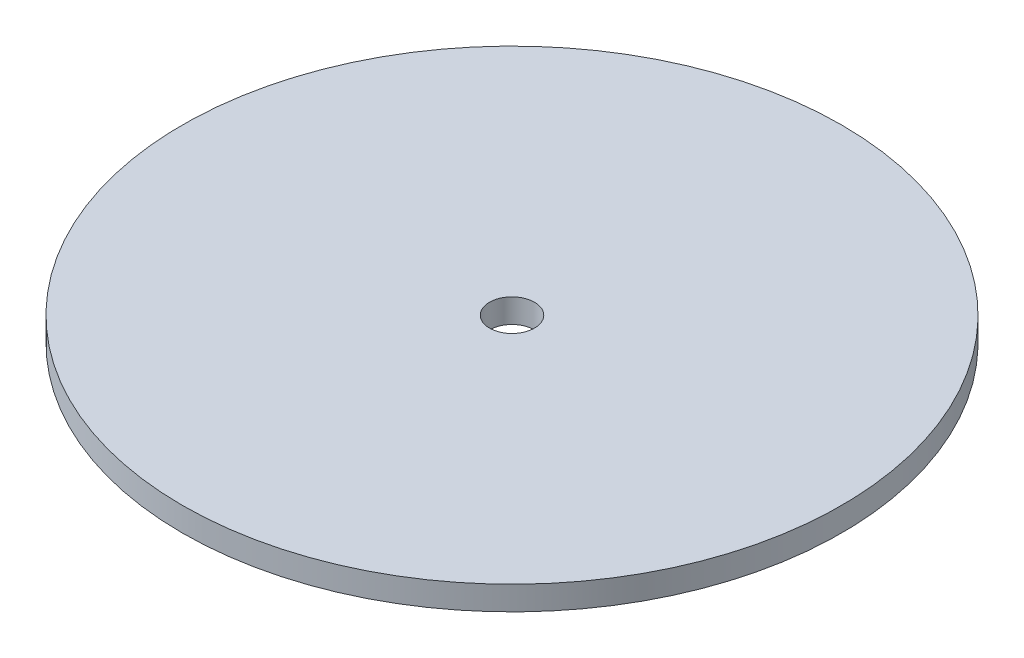
SolidWorks part; units mm, degrees
ref_plane "Front Plane" through (0, 0, 0) normal (0, 0, 1) x (1, 0, 0)
ref_plane "Top Plane" through (0, 0, 0) normal (0, 1, 0) x (1, 0, 0)
ref_plane "Right Plane" through (0, 0, 0) normal (1, 0, 0) x (0, 0, -1)
sketch "Sketch1" plane through (0, 0, 0) normal (0, 1, 0) x (1, 0, 0)
  circle A12 centre (0, 0) radius 110
  circle A13 centre (0, 0) radius 7.5
  dimension "D1" = 220
  dimension "D2" = 15
sketch "Sketch2" plane through (0, 0, 0) normal (0, 1, 0) x (1, 0, 0)
  line L0 (0, 111.3654) -> (0, -153.9587) construction
  circle A1 centre (0, 0) radius 45 construction
  circle A2 centre (0, 0) radius 110
  circle A3 centre (0, 45) radius 11.25
  circle A4 centre (22.5, 38.9711) radius 11.25
  circle A5 centre (38.9711, 22.5) radius 11.25
  circle A6 centre (45, 0) radius 11.25
  circle A7 centre (38.9711, -22.5) radius 11.25
  circle A8 centre (22.5, -38.9711) radius 11.25
  circle A9 centre (0, -45) radius 11.25
  circle A10 centre (-22.5, -38.9711) radius 11.25
  circle A11 centre (-38.9711, -22.5) radius 11.25
  circle A12 centre (-45, 0) radius 11.25
  circle A13 centre (0, 0) radius 7.5
  circle A14 centre (-38.9711, 22.5) radius 11.25
  circle A15 centre (-22.5, 38.9711) radius 11.25
  circle A16 centre (0, 90) radius 11.25
  circle A17 centre (27.8115, 85.5951) radius 11.25
  circle A18 centre (52.9007, 72.8115) radius 11.25
  circle A19 centre (72.8115, 52.9007) radius 11.25
  circle A20 centre (85.5951, 27.8115) radius 11.25
  circle A21 centre (90, 0) radius 11.25
  circle A22 centre (85.5951, -27.8115) radius 11.25
  circle A23 centre (72.8115, -52.9007) radius 11.25
  circle A24 centre (52.9007, -72.8115) radius 11.25
  circle A25 centre (27.8115, -85.5951) radius 11.25
  circle A26 centre (0, -90) radius 11.25
  circle A27 centre (-27.8115, -85.5951) radius 11.25
  circle A28 centre (-52.9007, -72.8115) radius 11.25
  circle A29 centre (-72.8115, -52.9007) radius 11.25
  circle A30 centre (-85.5951, -27.8115) radius 11.25
  circle A31 centre (-90, 0) radius 11.25
  circle A32 centre (-85.5951, 27.8115) radius 11.25
  circle A33 centre (-72.8115, 52.9007) radius 11.25
  circle A34 centre (-52.9007, 72.8115) radius 11.25
  circle A35 centre (-27.8115, 85.5951) radius 11.25
  circle A36 centre (0, 90) radius 20 construction
  circle A37 centre (0, 45) radius 20 construction
  point P3 (0, 7.5)
  point P8 (0, 56.25)
  point P27 (0, 0)
  point P77 (0, 0)
  dimension "D1" = 90
  dimension "D2" = 22.5
  dimension "D4" = 15
  dimension "D5" = 220
  dimension "D7" = 22.5
  dimension "D10" = 40
  dimension "D6" = 48.75
  dimension "D8" = 90
  dimension "D3" = 12
  dimension "D9" = 20
extrude "Boss-Extrude1" add sketch "Sketch2" against normal blind 5
extrude "Boss-Extrude2" add sketch "Sketch1" along normal blind 3
